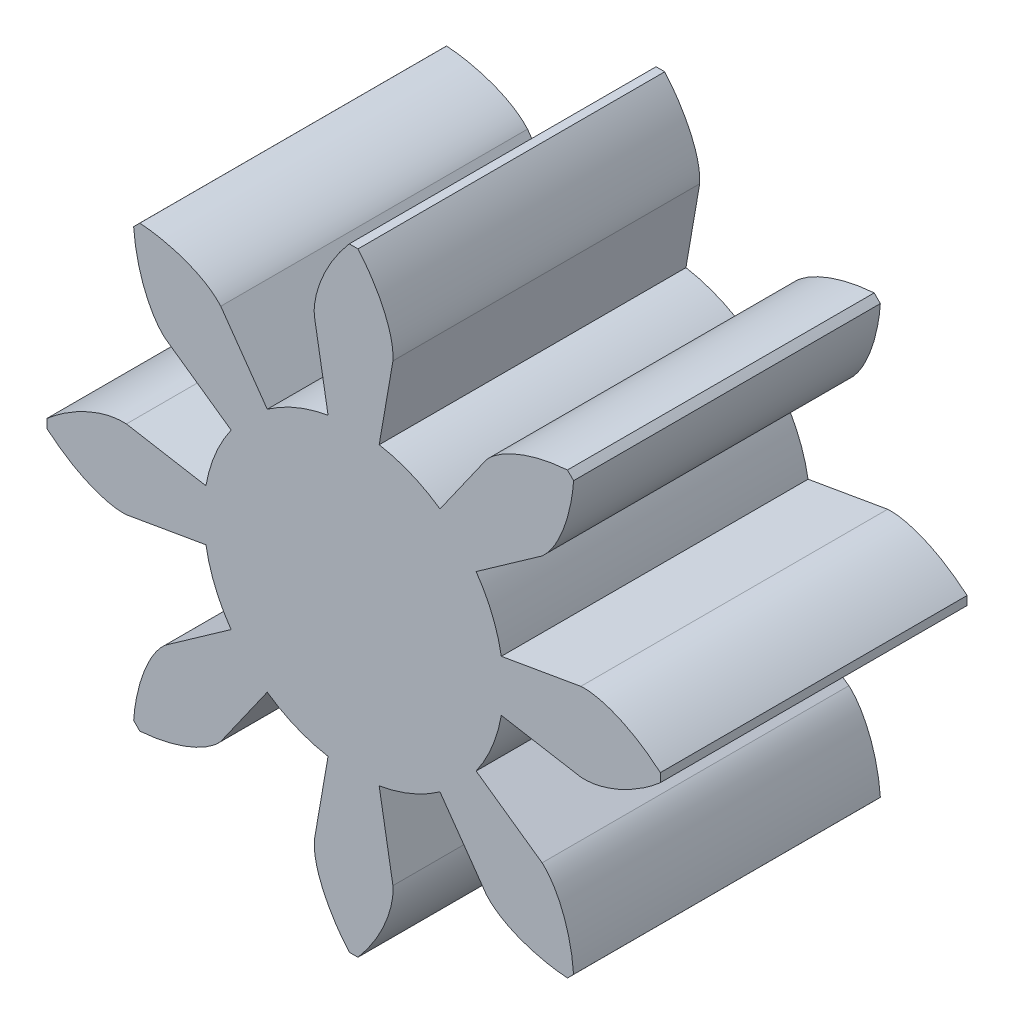
SolidWorks part; units mm, degrees
ref_plane "Front Plane" through (0, 0, 0) normal (0, 0, 1) x (1, 0, 0)
ref_plane "Top Plane" through (0, 0, 0) normal (0, 1, 0) x (1, 0, 0)
ref_plane "Right Plane" through (0, 0, 0) normal (1, 0, 0) x (0, 0, -1)
ref_plane "Plane1" through (0, 0, 5) normal (0, 0, 1) x (1, 0, 0)
sketch "Sketch1" plane through (0, 0, 5) normal (0, 0, 1) x (1, 0, 0)
  line L0 (0.4166, 2.4074) -> (0.6409, 3.7037)
  line L1 (-0.6409, 3.7037) -> (-0.4166, 2.4074)
  line L2 (-0.4166, 2.4074) -> (0.4166, 2.4074)
  arc A0 (0.0711, 4.9995) -> (-0.0711, 4.9995) centre (0, 0) ccw
  ellipse E0 centre (-0.2883, 4.4598) end of major axis (0.4985, 3.3938) minor radius 0.6183 (0.6409, 3.7037) -> (0.0711, 4.9995) ccw
  ellipse E1 centre (0.226, 4.4514) end of major axis (-0.5063, 3.4168) minor radius 0.5729 (-0.0711, 4.9995) -> (-0.6409, 3.7037) ccw
  point P2 (-0.2883, 4.4598)
  point P3 (0.2092, 4.827)
  point P4 (0.4985, 3.3938)
  point P5 (0.6409, 3.7037)
  point P6 (0.0711, 4.9995)
  point P7 (0.4689, 4.3983)
  point P8 (-1.0455, 4.5213)
  point P17 (0.226, 4.4514)
  point P18 (0.6936, 4.1205)
  point P19 (-0.5063, 3.4168)
  point P20 (-0.0711, 4.9995)
  point P21 (-0.6409, 3.7037)
  point P22 (-0.4689, 4.3983)
  point P23 (0.9209, 4.5046)
extrude "Boss-Extrude1" add sketch "Sketch1" against normal blind 5
ref_axis "Axis1" through (0, 0, 0) along (0, 0, 1)
pattern_circular "CirPattern1" count 8 over 360 about axis through (0, 0, 0) along (0, 0, 1) of "Boss-Extrude1"
sketch "Sketch2" plane through (0, 0, 5) normal (0, 0, 1) x (1, 0, 0)
  circle A0 centre (0, 0) radius 2.4432
extrude "Boss-Extrude2" add sketch "Sketch2" against normal up to surface (5 mm away) up to face at (0, 3.6954, 0)
